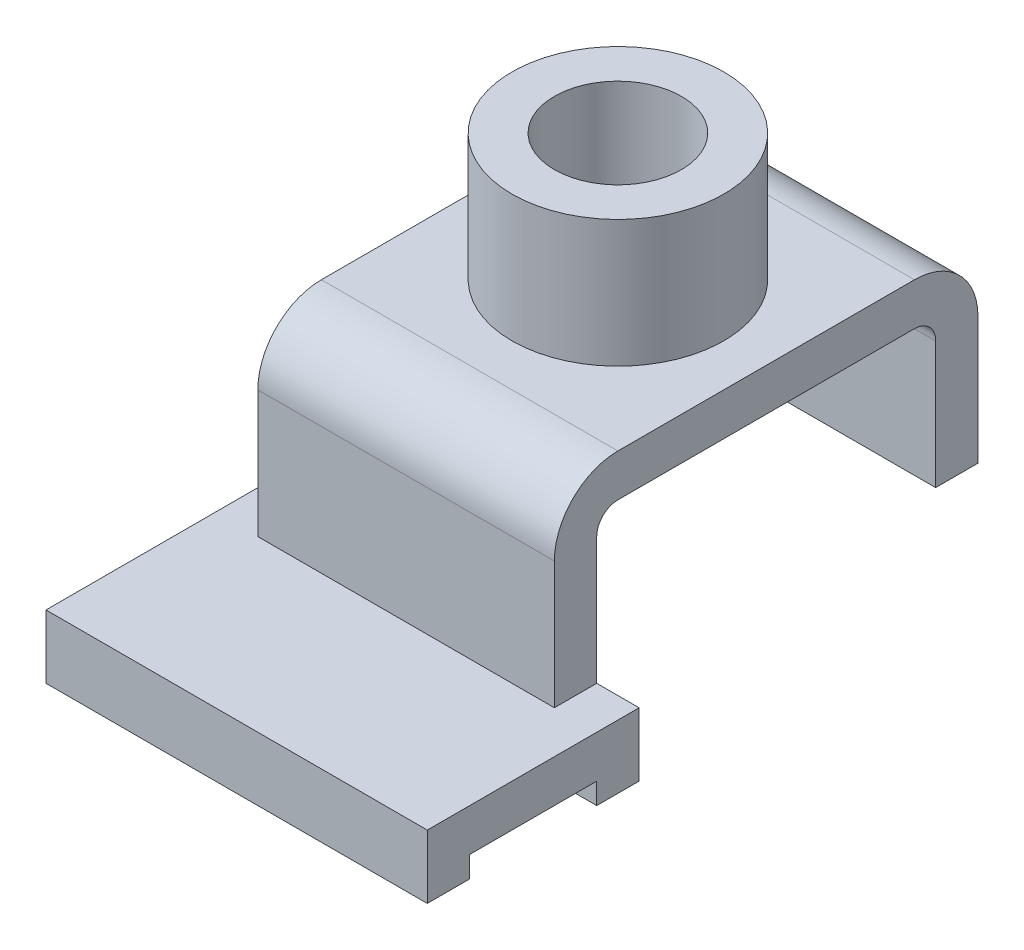
SolidWorks part; units mm, degrees
ref_plane "Front Plane" through (0, 0, 0) normal (0, 0, 1) x (1, 0, 0)
ref_plane "Top Plane" through (0, 0, 0) normal (0, 1, 0) x (1, 0, 0)
ref_plane "Right Plane" through (0, 0, 0) normal (1, 0, 0) x (0, 0, -1)
sketch "Sketch1" plane through (0, 0, 0) normal (1, 0, 0) x (0, 0, -1)
  line L0 (-20.6429, -6.6429) -> (-30.6429, -6.6429)
  line L1 (-30.6429, -6.6429) -> (-30.6429, 8.3571)
  line L2 (-30.6429, 8.3571) -> (19.3571, 8.3571)
  line L3 (19.3571, 8.3571) -> (19.3571, -6.6429)
  line L4 (19.3571, -6.6429) -> (9.3571, -6.6429)
  line L5 (9.3571, -6.6429) -> (9.3571, -1.6429)
  line L6 (9.3571, -1.6429) -> (-20.6429, -1.6429)
  line L7 (-20.6429, -1.6429) -> (-20.6429, -6.6429)
  point P9 (-5.6429, 8.3571)
  dimension "D1" = 30
  dimension "D2" = 10
  dimension "D3" = 10
  dimension "D4" = 15
  dimension "D5" = 15
  dimension "D6" = 10
  dimension "D7" = 5
extrude "Boss-Extrude1" add sketch "Sketch1" against normal mid plane 90
sketch "Sketch2" plane through (45, 0, 0) normal (1, 0, 0) x (0, 0, -1)
  line L0 (19.3571, 8.3571) -> (19.3571, 38.3571)
  line L1 (24.3571, 43.3571) -> (94.3571, 43.3571)
  line L2 (99.3571, 38.3571) -> (99.3571, 8.3571)
  line L3 (99.3571, 8.3571) -> (109.3571, 8.3571)
  line L4 (109.3571, 8.3571) -> (109.3571, 38.3571)
  line L5 (94.3571, 53.3571) -> (24.3571, 53.3571)
  line L6 (9.3571, 38.3571) -> (9.3571, 8.3571)
  line L7 (19.3571, 8.3571) -> (-30.6429, 8.3571) construction
  line L8 (9.3571, 8.3571) -> (19.3571, 8.3571)
  line L9 (9.3571, -6.6429) -> (19.3571, -6.6429) construction
  arc A0 (99.3571, 38.3571) -> (94.3571, 43.3571) centre (94.3571, 38.3571) ccw
  arc A1 (24.3571, 43.3571) -> (19.3571, 38.3571) centre (24.3571, 38.3571) ccw
  arc A2 (109.3571, 38.3571) -> (94.3571, 53.3571) centre (94.3571, 38.3571) ccw
  arc A3 (24.3571, 53.3571) -> (9.3571, 38.3571) centre (24.3571, 38.3571) ccw
  dimension "D5" = 5
  dimension "D6" = 15
  dimension "D1" = 80
  dimension "D2" = 10
  dimension "D3" = 10
  dimension "D4" = 10
  dimension "D7" = 50
extrude "Boss-Extrude2" add sketch "Sketch2" against normal blind 70 from offset 10 offset against normal yes
sketch "Sketch3" plane through (0, 53.3571, 0) normal (0, 1, 0) x (1, 0, 0)
  circle A0 centre (0, 59.3571) radius 25
  circle A1 centre (0, 59.3571) radius 15
  dimension "D1" = 50
  dimension "D2" = 30
extrude "Boss-Extrude3" add sketch "Sketch3" along normal blind 30
